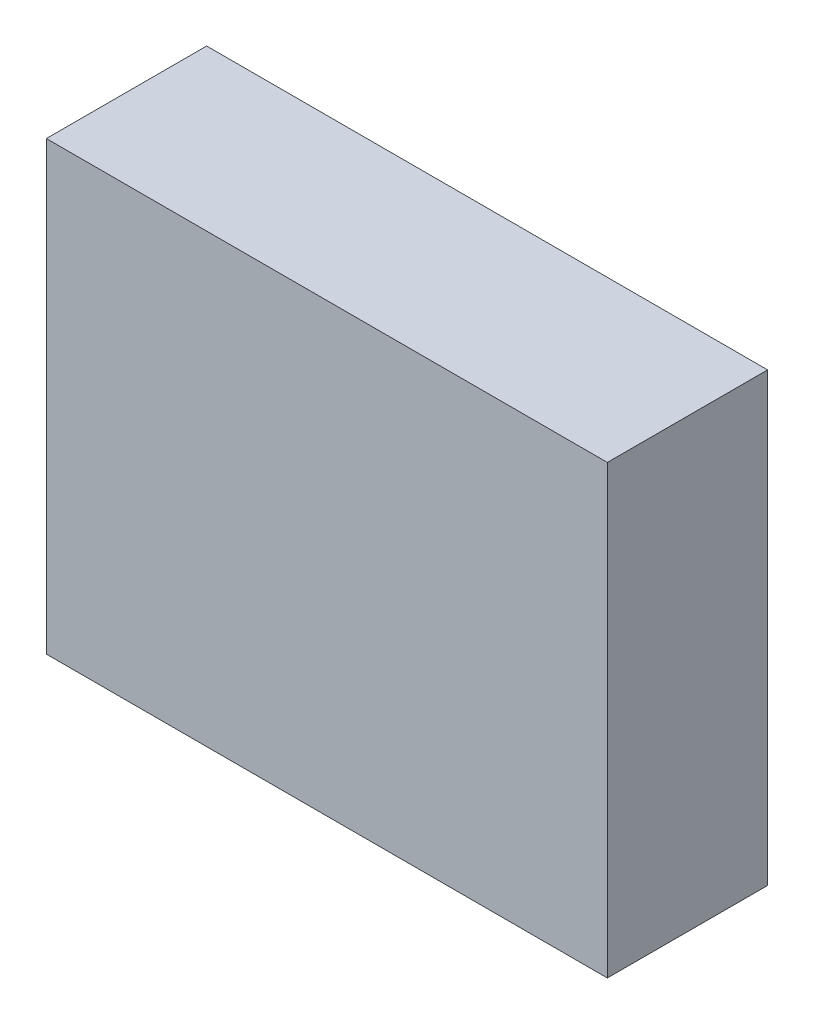
SolidWorks part; units mm, degrees
material "ABS"
ref_plane "Front Plane" through (0, 0, 0) normal (0, 0, 1) x (1, 0, 0)
ref_plane "Top Plane" through (0, 0, 0) normal (0, 1, 0) x (1, 0, 0)
ref_plane "Right Plane" through (0, 0, 0) normal (1, 0, 0) x (0, 0, -1)
sketch "Body" plane through (0, 0, 0) normal (0, 0, 1) x (1, 0, 0)
  line L1 (-2.45, 1.95) -> (2.45, 1.95)
  line L2 (-2.45, 1.95) -> (-2.45, -1.95)
  line L3 (-2.45, -1.95) -> (2.45, -1.95)
  line L4 (2.45, 1.95) -> (2.45, -1.95)
  line L5 (0, -1.95) -> (0, 1.95) construction
  line L6 (-2.45, 0) -> (2.45, 0) construction
  point P0 (0, 0)
  dimension "D1" = 3.9
  dimension "D2" = 4.9
extrude "Boss-Extrude1" add sketch "Body" along normal blind 1.4
